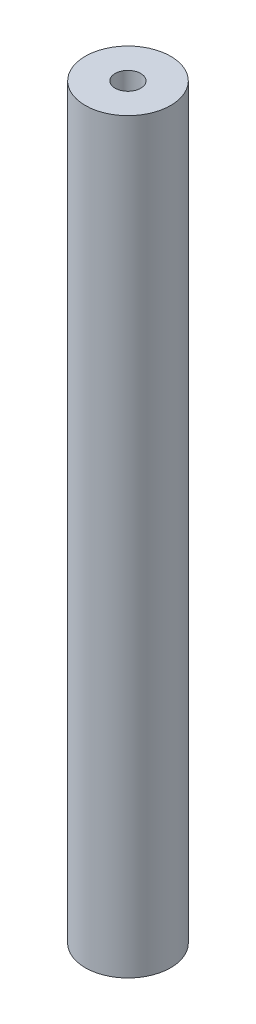
SolidWorks part; units mm, degrees
ref_plane "Front Plane" through (0, 0, 0) normal (0, 0, 1) x (1, 0, 0)
ref_plane "Top Plane" through (0, 0, 0) normal (0, 1, 0) x (1, 0, 0)
ref_plane "Right Plane" through (0, 0, 0) normal (1, 0, 0) x (0, 0, -1)
sketch "Sketch1" plane through (0, 0, 0) normal (0, 1, 0) x (1, 0, 0)
  circle A0 centre (0, 0) radius 5.08
  dimension "D1" = 10.16
extrude "Boss-Extrude1" add sketch "Sketch1" along normal blind 88.9
hole_wizard "Tapped Hole for #4-40 Helicoil1" positions "Sketch2" profile "Sketch4" tap size "#4-40" standard "Helicoil® Inch"
sketch "Sketch2" plane through (0, 88.9, 0) normal (0, 1, 0) x (1, 0, 0)
  point P0 (0, 0)
sketch "Sketch4" plane through (0, 88.9, 0) normal (1, 0, 0) x (0, 0, 1)
  line L0 (0, 0) -> (0, 9.0437)
  line L1 (0, 9.0437) -> (1.524, 8.128)
  line L2 (1.524, 8.128) -> (1.524, 0)
  line L5 (1.524, 0) -> (0, 0)
  line L10 (0, 9.0437) -> (-1.524, 8.128) construction
  line L11 (0, -6.35) -> (0, 107.95) construction
  dimension "Tap Drill Dia." = 3.048
  dimension "Tap Drill Depth" = 8.128
  dimension "Drill Angle" = 118
cosmetic thread "Hole Thread1" parameters "D1"=3.556, "D2"=3.7414
hole_wizard "Tapped Hole for #4-40 Helicoil2" positions "Sketch7" profile "Sketch6" tap size "#4-40" standard "Helicoil® Inch"
sketch "Sketch7" plane through (0, 0, 0) normal (0, -1, 0) x (-1, 0, 0)
  point P0 (0, 0)
sketch "Sketch6" plane through (0, 0, 0) normal (1, 0, 0) x (0, 0, -1)
  line L0 (0, 0) -> (0, 9.0437)
  line L1 (0, 9.0437) -> (1.524, 8.128)
  line L2 (1.524, 8.128) -> (1.524, 0)
  line L5 (1.524, 0) -> (0, 0)
  line L10 (0, 9.0437) -> (-1.524, 8.128) construction
  line L11 (0, -6.35) -> (0, 107.95) construction
  dimension "Tap Drill Dia." = 3.048
  dimension "Tap Drill Depth" = 8.128
  dimension "Drill Angle" = 118
cosmetic thread "Hole Thread2" parameters "D1"=3.556, "D2"=3.7414
